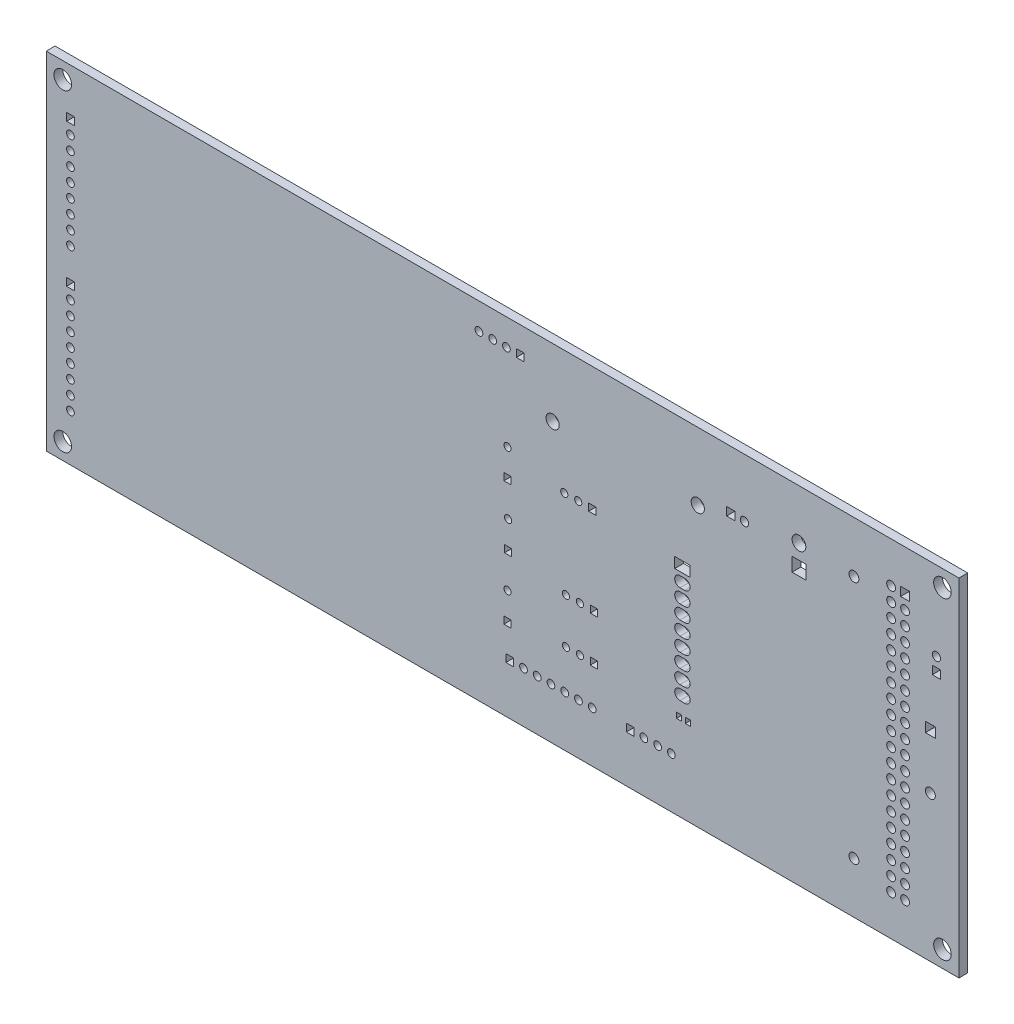
SolidWorks part; units mm, degrees
material "Silicon"
ref_plane "Front Plane" through (0, 0, 0) normal (0, 0, 1) x (1, 0, 0)
ref_plane "Top Plane" through (0, 0, 0) normal (0, 1, 0) x (1, 0, 0)
ref_plane "Right Plane" through (0, 0, 0) normal (1, 0, 0) x (0, 0, -1)
sketch "Sketch1" plane through (0, 0, 0) normal (0, 0, 1) x (1, 0, 0)
  line L0 (98.95, 20.25) -> (100.25, 20.25)
  line L129 (159.9, 32.4) -> (161.7, 32.4)
  line L130 (161.7, 32.4) -> (161.7, 30.6)
  line L131 (161.7, 30.6) -> (159.9, 30.6)
  line L132 (159.9, 30.6) -> (159.9, 32.4)
  line L201 (114.303, 35.5525) -> (117.097, 35.5525)
  line L202 (117.097, 35.5525) -> (117.097, 33.6475)
  line L203 (117.097, 33.6475) -> (114.303, 33.6475)
  line L204 (114.303, 33.6475) -> (114.303, 35.5525)
  line L205 (116.1445, 31.1075) -> (115.2555, 31.1075)
  line L206 (115.2555, 33.0125) -> (116.1445, 33.0125)
  line L207 (116.1445, 28.5675) -> (115.2555, 28.5675)
  line L208 (115.2555, 30.4725) -> (116.1445, 30.4725)
  line L209 (116.1445, 26.0275) -> (115.2555, 26.0275)
  line L210 (115.2555, 27.9325) -> (116.1445, 27.9325)
  line L211 (116.1445, 23.4875) -> (115.2555, 23.4875)
  line L212 (115.2555, 25.3925) -> (116.1445, 25.3925)
  line L213 (116.1445, 20.9475) -> (115.2555, 20.9475)
  line L214 (115.2555, 22.8525) -> (116.1445, 22.8525)
  line L215 (116.1445, 18.4075) -> (115.2555, 18.4075)
  line L216 (115.2555, 20.3125) -> (116.1445, 20.3125)
  line L217 (116.1445, 15.8675) -> (115.2555, 15.8675)
  line L218 (115.2555, 17.7725) -> (116.1445, 17.7725)
  line L219 (116.1445, 13.3275) -> (115.2555, 13.3275)
  line L220 (115.2555, 15.2325) -> (116.1445, 15.2325)
  line L261 (3.7, 24.2) -> (5.1, 24.2)
  line L262 (5.1, 24.2) -> (5.1, 22.8)
  line L263 (5.1, 22.8) -> (3.7, 22.8)
  line L264 (3.7, 22.8) -> (3.7, 24.2)
  line L265 (3.7, 50.2) -> (5.1, 50.2)
  line L266 (5.1, 50.2) -> (5.1, 48.8)
  line L267 (5.1, 48.8) -> (3.7, 48.8)
  line L268 (3.7, 48.8) -> (3.7, 50.2)
  line L501 (100.25, 12.05) -> (100.25, 10.75)
  line L502 (100.25, 10.75) -> (98.95, 10.75)
  line L503 (98.95, 10.75) -> (98.95, 12.05)
  line L504 (98.95, 12.05) -> (100.25, 12.05)
  line L505 (100.25, 20.25) -> (100.25, 18.95)
  line L506 (100.25, 18.95) -> (98.95, 18.95)
  line L507 (98.95, 18.95) -> (98.95, 20.25)
  line L509 (99.95, 36.15) -> (99.95, 34.85)
  line L510 (99.95, 34.85) -> (98.65, 34.85)
  line L511 (98.65, 34.85) -> (98.65, 36.15)
  line L512 (98.65, 36.15) -> (99.95, 36.15)
  line L577 (84.55, 9.35) -> (83.25, 9.35)
  line L578 (83.25, 9.35) -> (83.25, 10.65)
  line L579 (83.25, 10.65) -> (84.55, 10.65)
  line L580 (84.55, 10.65) -> (84.55, 9.35)
  line L581 (84.65, 20.65) -> (83.35, 20.65)
  line L582 (83.35, 20.65) -> (83.35, 21.95)
  line L583 (83.35, 21.95) -> (84.65, 21.95)
  line L584 (84.65, 21.95) -> (84.65, 20.65)
  line L585 (84.55, 31.95) -> (83.25, 31.95)
  line L586 (83.25, 31.95) -> (83.25, 33.25)
  line L587 (83.25, 33.25) -> (84.55, 33.25)
  line L588 (84.55, 33.25) -> (84.55, 31.95)
  line L589 (162.65, 40.3499) -> (161.1499, 40.3499)
  line L590 (161.1499, 40.3499) -> (161.1499, 41.8501)
  line L591 (161.1499, 41.8501) -> (162.65, 41.8501)
  line L592 (162.65, 41.8501) -> (162.65, 40.3499)
  line L593 (123.7499, 46.6499) -> (123.7499, 48.15)
  line L594 (123.7499, 48.15) -> (125.25, 48.15)
  line L595 (125.25, 48.15) -> (125.25, 46.6499)
  line L596 (125.25, 46.6499) -> (123.7499, 46.6499)
  line L597 (138.15, 43.75) -> (135.65, 43.75)
  line L598 (135.65, 43.75) -> (135.65, 46.25)
  line L599 (135.65, 46.25) -> (138.15, 46.25)
  line L600 (138.15, 46.25) -> (138.15, 43.75)
  line L601 (83.6, 3.5) -> (83.6, 4.9)
  line L602 (83.6, 4.9) -> (85, 4.9)
  line L603 (85, 4.9) -> (85, 3.5)
  line L604 (85, 3.5) -> (83.6, 3.5)
  line L605 (86.9, 53.9) -> (86.9, 52.5)
  line L606 (86.9, 52.5) -> (85.5, 52.5)
  line L607 (85.5, 52.5) -> (85.5, 53.9)
  line L608 (85.5, 53.9) -> (86.9, 53.9)
  line L609 (105.5, 3.5) -> (105.5, 4.9)
  line L610 (105.5, 4.9) -> (106.9, 4.9)
  line L611 (106.9, 4.9) -> (106.9, 3.5)
  line L612 (106.9, 3.5) -> (105.5, 3.5)
  line L1605 (115.575, 10.2) -> (114.625, 10.2)
  line L1606 (114.625, 10.2) -> (114.625, 11.2)
  line L1607 (114.625, 11.2) -> (115.575, 11.2)
  line L1608 (115.575, 11.2) -> (115.575, 10.2)
  line L1609 (117.175, 10.2) -> (116.225, 10.2)
  line L1610 (116.225, 10.2) -> (116.225, 11.2)
  line L1611 (116.225, 11.2) -> (117.175, 11.2)
  line L1612 (117.175, 11.2) -> (117.175, 10.2)
  line L1725 (157, 51.4) -> (155.4, 51.4)
  line L1726 (155.4, 51.4) -> (155.4, 49.8)
  line L1727 (155.4, 49.8) -> (157, 49.8)
  line L1728 (157, 49.8) -> (157, 51.4)
  line L1729 (0, -5) -> (0, 58)
  line L1730 (0, 58) -> (166, 58)
  line L1731 (166, 58) -> (166, -5)
  line L1732 (166, -5) -> (0, -5)
  circle A88 centre (3, -2) radius 1.6
  circle A89 centre (3, 55) radius 1.6
  circle A90 centre (163, -2) radius 1.5999
  circle A91 centre (163, 55) radius 1.5999
  circle A92 centre (160.8, 21.5) radius 0.9
  arc A109 (115.2555, 33.0125) -> (115.2555, 31.1075) centre (115.2555, 32.06) ccw
  arc A110 (116.1445, 31.1075) -> (116.1445, 33.0125) centre (116.1445, 32.06) ccw
  arc A111 (115.2555, 30.4725) -> (115.2555, 28.5675) centre (115.2555, 29.52) ccw
  arc A112 (116.1445, 28.5675) -> (116.1445, 30.4725) centre (116.1445, 29.52) ccw
  arc A113 (115.2555, 27.9325) -> (115.2555, 26.0275) centre (115.2555, 26.98) ccw
  arc A114 (116.1445, 26.0275) -> (116.1445, 27.9325) centre (116.1445, 26.98) ccw
  arc A115 (115.2555, 25.3925) -> (115.2555, 23.4875) centre (115.2555, 24.44) ccw
  arc A116 (116.1445, 23.4875) -> (116.1445, 25.3925) centre (116.1445, 24.44) ccw
  arc A117 (115.2555, 22.8525) -> (115.2555, 20.9475) centre (115.2555, 21.9) ccw
  arc A118 (116.1445, 20.9475) -> (116.1445, 22.8525) centre (116.1445, 21.9) ccw
  arc A119 (115.2555, 20.3125) -> (115.2555, 18.4075) centre (115.2555, 19.36) ccw
  arc A120 (116.1445, 18.4075) -> (116.1445, 20.3125) centre (116.1445, 19.36) ccw
  arc A121 (115.2555, 17.7725) -> (115.2555, 15.8675) centre (115.2555, 16.82) ccw
  arc A122 (116.1445, 15.8675) -> (116.1445, 17.7725) centre (116.1445, 16.82) ccw
  arc A123 (115.2555, 15.2325) -> (115.2555, 13.3275) centre (115.2555, 14.28) ccw
  arc A124 (116.1445, 13.3275) -> (116.1445, 15.2325) centre (116.1445, 14.28) ccw
  circle A125 centre (4.4, 21) radius 0.7
  circle A126 centre (4.4, 18.5) radius 0.7
  circle A127 centre (4.4, 16) radius 0.7
  circle A128 centre (4.4, 13.5) radius 0.7
  circle A129 centre (4.4, 11) radius 0.7
  circle A130 centre (4.4, 8.5) radius 0.7
  circle A131 centre (4.4, 6) radius 0.7
  circle A132 centre (4.4, 3.5) radius 0.7
  circle A133 centre (4.4, 47) radius 0.7
  circle A134 centre (4.4, 44.5) radius 0.7
  circle A135 centre (4.4, 42) radius 0.7
  circle A136 centre (4.4, 39.5) radius 0.7
  circle A137 centre (4.4, 37) radius 0.7
  circle A138 centre (4.4, 34.5) radius 0.7
  circle A139 centre (4.4, 32) radius 0.7
  circle A140 centre (4.4, 29.5) radius 0.7
  circle A357 centre (97.06, 11.4) radius 0.65
  circle A358 centre (94.52, 11.4) radius 0.65
  circle A359 centre (97.06, 19.6) radius 0.65
  circle A360 centre (94.52, 19.6) radius 0.65
  circle A361 centre (96.76, 35.5) radius 0.65
  circle A362 centre (94.22, 35.5) radius 0.65
  circle A363 centre (92.1, 45.7) radius 1.2
  circle A364 centre (118.5, 45.7) radius 1.2
  circle A365 centre (83.9, 15) radius 0.65
  circle A366 centre (84, 26.3) radius 0.65
  circle A367 centre (83.9, 37.6) radius 0.65
  circle A368 centre (161.9, 43.6) radius 0.7501
  circle A369 centre (127, 47.4) radius 0.7501
  circle A370 centre (136.9, 48.96) radius 1.25
  circle A371 centre (86.8, 4.2) radius 0.7
  circle A372 centre (89.3, 4.2) radius 0.7
  circle A373 centre (91.8, 4.2) radius 0.7
  circle A374 centre (94.3, 4.2) radius 0.7
  circle A375 centre (96.8, 4.2) radius 0.7
  circle A376 centre (99.3, 4.2) radius 0.7
  circle A377 centre (83.7, 53.2) radius 0.7
  circle A378 centre (81.2, 53.2) radius 0.7
  circle A379 centre (78.7, 53.2) radius 0.7
  circle A380 centre (108.7, 4.2) radius 0.7
  circle A381 centre (111.2, 4.2) radius 0.7
  circle A382 centre (113.7, 4.2) radius 0.7
  circle A383 centre (153.66, 50.6) radius 0.8
  circle A384 centre (156.2, 48.06) radius 0.8
  circle A385 centre (153.66, 48.06) radius 0.8
  circle A386 centre (156.2, 45.52) radius 0.8
  circle A387 centre (153.66, 45.52) radius 0.8
  circle A388 centre (156.2, 42.98) radius 0.8
  circle A389 centre (153.66, 42.98) radius 0.8
  circle A390 centre (156.2, 40.44) radius 0.8
  circle A391 centre (153.66, 40.44) radius 0.8
  circle A392 centre (156.2, 37.9) radius 0.8
  circle A393 centre (153.66, 37.9) radius 0.8
  circle A394 centre (156.2, 35.36) radius 0.8
  circle A395 centre (153.66, 35.36) radius 0.8
  circle A396 centre (156.2, 32.82) radius 0.8
  circle A397 centre (153.66, 32.82) radius 0.8
  circle A398 centre (156.2, 30.28) radius 0.8
  circle A399 centre (153.66, 30.28) radius 0.8
  circle A400 centre (156.2, 27.74) radius 0.8
  circle A401 centre (153.66, 27.74) radius 0.8
  circle A402 centre (156.2, 25.2) radius 0.8
  circle A403 centre (153.66, 25.2) radius 0.8
  circle A404 centre (156.2, 22.66) radius 0.8
  circle A405 centre (153.66, 22.66) radius 0.8
  circle A406 centre (156.2, 20.12) radius 0.8
  circle A407 centre (153.66, 20.12) radius 0.8
  circle A408 centre (156.2, 17.58) radius 0.8
  circle A409 centre (153.66, 17.58) radius 0.8
  circle A410 centre (156.2, 15.04) radius 0.8
  circle A411 centre (153.66, 15.04) radius 0.8
  circle A412 centre (156.2, 12.5) radius 0.8
  circle A413 centre (153.66, 12.5) radius 0.8
  circle A414 centre (156.2, 9.96) radius 0.8
  circle A415 centre (153.66, 9.96) radius 0.8
  circle A416 centre (156.2, 7.42) radius 0.8
  circle A417 centre (153.66, 7.42) radius 0.8
  circle A418 centre (156.2, 4.88) radius 0.8
  circle A419 centre (153.66, 4.88) radius 0.8
  circle A420 centre (156.2, 2.34) radius 0.8
  circle A421 centre (153.66, 2.34) radius 0.8
  circle A422 centre (146.9, 48.7) radius 0.9
  circle A423 centre (146.9, 4.3) radius 0.9
extrude "Boss-Extrude1" add sketch "Sketch1" along normal blind 1.6
